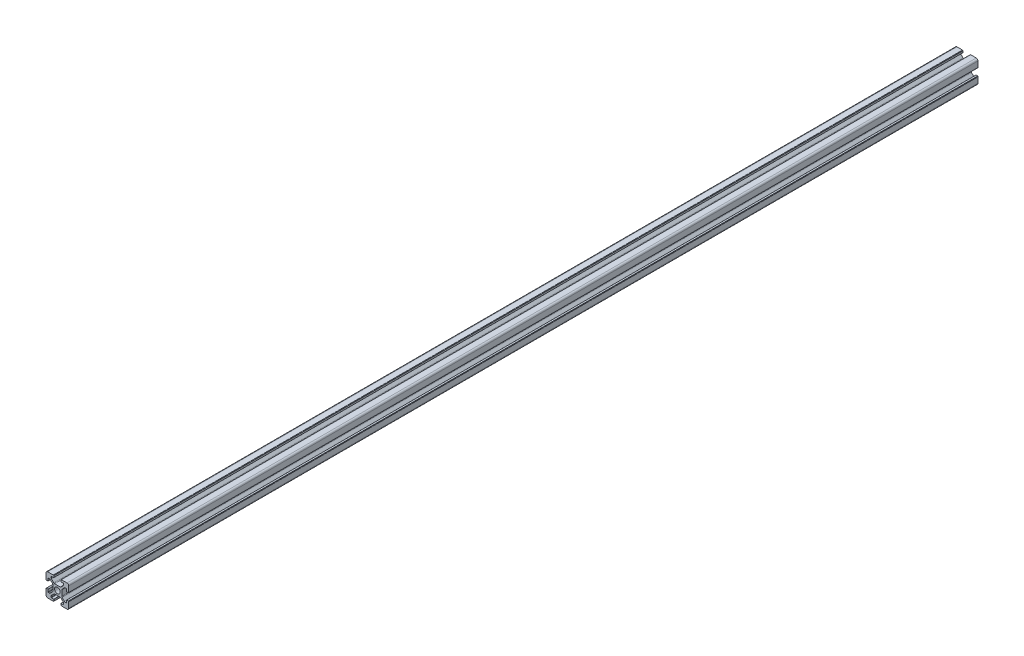
SolidWorks part; units mm, degrees
material "6063-T5"
ref_plane "前视基准面" through (0, 0, 0) normal (0, 0, 1) x (1, 0, 0)
ref_plane "上视基准面" through (0, 0, 0) normal (0, 1, 0) x (1, 0, 0)
ref_plane "右视基准面" through (0, 0, 0) normal (1, 0, 0) x (0, 0, -1)
sketch "草图1" plane through (0, 0, 0) normal (0, 0, 1) x (1, 0, 0)
  line L0 (-1.4389, 10) -> (24.3741, 10) construction
  line L1 (20, 13.6) -> (20, 20)
  line L2 (0, 0) -> (0, 6.4)
  line L3 (0, 20) -> (6.4, 20)
  line L4 (20, 0) -> (20, 6.4)
  line L5 (10, 21.5388) -> (10, -2.4017) construction
  line L6 (6.9, 18.3) -> (6.9, 19.7)
  line L7 (6.8, 18.2) -> (4.8, 18.2)
  line L8 (4.5, 17.9) -> (4.5, 16.9749)
  line L9 (4.7929, 16.2678) -> (6.8678, 14.1929)
  line L10 (7.5749, 13.9) -> (12.4251, 13.9)
  line L11 (6.8, 19.8) -> (6.4, 19.8)
  line L12 (6.4, 19.8) -> (6.4, 20)
  line L13 (0, 13.6) -> (0.2, 13.6)
  line L14 (0.2, 13.6) -> (0.2, 13.2)
  line L15 (0.3, 13.1) -> (1.7, 13.1)
  line L16 (1.8, 13.2) -> (1.8, 15.2)
  line L17 (2.1, 15.5) -> (3.0251, 15.5)
  line L18 (3.7322, 15.2071) -> (5.8071, 13.1322)
  line L19 (6.1, 12.4251) -> (6.1, 7.5749)
  line L20 (13.6, 19.8) -> (13.6, 20)
  line L21 (13.2, 19.8) -> (13.6, 19.8)
  line L22 (13.1, 18.3) -> (13.1, 19.7)
  line L23 (13.2, 18.2) -> (15.2, 18.2)
  line L24 (15.5, 17.9) -> (15.5, 16.9749)
  line L25 (15.2071, 16.2678) -> (13.1322, 14.1929)
  line L26 (0, 6.4) -> (0.2, 6.4)
  line L27 (0.2, 6.4) -> (0.2, 6.8)
  line L28 (0.3, 6.9) -> (1.7, 6.9)
  line L29 (1.8, 6.8) -> (1.8, 4.8)
  line L30 (2.1, 4.5) -> (3.0251, 4.5)
  line L31 (3.7322, 4.7929) -> (5.8071, 6.8678)
  line L32 (13.6, 20) -> (20, 20)
  line L33 (0, 13.6) -> (0, 20)
  line L34 (13.6, 0.2) -> (13.6, 0)
  line L35 (13.2, 0.2) -> (13.6, 0.2)
  line L36 (13.1, 1.7) -> (13.1, 0.3)
  line L37 (13.2, 1.8) -> (15.2, 1.8)
  line L38 (15.5, 2.1) -> (15.5, 3.0251)
  line L39 (15.2071, 3.7322) -> (13.1322, 5.8071)
  line L40 (4.5, 2.1) -> (4.5, 3.0251)
  line L41 (6.8, 1.8) -> (4.8, 1.8)
  line L42 (6.4, 0.2) -> (6.4, 0)
  line L43 (6.8, 0.2) -> (6.4, 0.2)
  line L44 (6.9, 1.7) -> (6.9, 0.3)
  line L45 (4.7929, 3.7322) -> (6.8678, 5.8071)
  line L46 (7.5749, 6.1) -> (12.4251, 6.1)
  line L47 (20, 6.4) -> (19.8, 6.4)
  line L48 (19.8, 6.4) -> (19.8, 6.8)
  line L49 (19.7, 6.9) -> (18.3, 6.9)
  line L50 (18.2, 6.8) -> (18.2, 4.8)
  line L51 (17.9, 4.5) -> (16.9749, 4.5)
  line L52 (16.2678, 4.7929) -> (14.1929, 6.8678)
  line L53 (13.9, 12.4251) -> (13.9, 7.5749)
  line L54 (16.2678, 15.2071) -> (14.1929, 13.1322)
  line L55 (17.9, 15.5) -> (16.9749, 15.5)
  line L56 (18.2, 13.2) -> (18.2, 15.2)
  line L57 (19.7, 13.1) -> (18.3, 13.1)
  line L58 (19.8, 13.6) -> (19.8, 13.2)
  line L59 (20, 13.6) -> (19.8, 13.6)
  line L60 (0, 0) -> (6.4, 0)
  line L61 (13.6, 0) -> (20, 0)
  arc A0 (6.1, 12.4251) -> (5.8071, 13.1322) centre (5.1, 12.4251) ccw
  arc A1 (7.5749, 13.9) -> (6.8678, 14.1929) centre (7.5749, 14.9) cw
  arc A2 (4.5, 16.9749) -> (4.7929, 16.2678) centre (5.5, 16.9749) ccw
  arc A3 (3.7322, 15.2071) -> (3.0251, 15.5) centre (3.0251, 14.5) ccw
  arc A4 (4.5, 17.9) -> (4.8, 18.2) centre (4.8, 17.9) cw
  arc A5 (1.8, 15.2) -> (2.1, 15.5) centre (2.1, 15.2) cw
  arc A6 (0.3, 13.1) -> (0.2, 13.2) centre (0.3, 13.2) cw
  arc A7 (6.9, 19.7) -> (6.8, 19.8) centre (6.8, 19.7) ccw
  arc A8 (1.7, 13.1) -> (1.8, 13.2) centre (1.7, 13.2) ccw
  arc A9 (6.9, 18.3) -> (6.8, 18.2) centre (6.8, 18.3) cw
  arc A10 (13.1, 19.7) -> (13.2, 19.8) centre (13.2, 19.7) cw
  arc A11 (13.1, 18.3) -> (13.2, 18.2) centre (13.2, 18.3) ccw
  arc A12 (15.5, 17.9) -> (15.2, 18.2) centre (15.2, 17.9) ccw
  arc A13 (15.5, 16.9749) -> (15.2071, 16.2678) centre (14.5, 16.9749) cw
  arc A14 (12.4251, 13.9) -> (13.1322, 14.1929) centre (12.4251, 14.9) ccw
  arc A15 (0.3, 6.9) -> (0.2, 6.8) centre (0.3, 6.8) ccw
  arc A16 (1.7, 6.9) -> (1.8, 6.8) centre (1.7, 6.8) cw
  arc A17 (1.8, 4.8) -> (2.1, 4.5) centre (2.1, 4.8) ccw
  arc A18 (3.7322, 4.7929) -> (3.0251, 4.5) centre (3.0251, 5.5) cw
  arc A19 (6.1, 7.5749) -> (5.8071, 6.8678) centre (5.1, 7.5749) cw
  arc A20 (13.1, 0.3) -> (13.2, 0.2) centre (13.2, 0.3) ccw
  arc A21 (13.1, 1.7) -> (13.2, 1.8) centre (13.2, 1.7) cw
  arc A22 (15.5, 2.1) -> (15.2, 1.8) centre (15.2, 2.1) cw
  arc A23 (15.5, 3.0251) -> (15.2071, 3.7322) centre (14.5, 3.0251) ccw
  arc A24 (12.4251, 6.1) -> (13.1322, 5.8071) centre (12.4251, 5.1) cw
  arc A25 (4.5, 2.1) -> (4.8, 1.8) centre (4.8, 2.1) ccw
  arc A26 (6.9, 0.3) -> (6.8, 0.2) centre (6.8, 0.3) cw
  arc A27 (6.9, 1.7) -> (6.8, 1.8) centre (6.8, 1.7) ccw
  arc A28 (4.5, 3.0251) -> (4.7929, 3.7322) centre (5.5, 3.0251) cw
  arc A29 (7.5749, 6.1) -> (6.8678, 5.8071) centre (7.5749, 5.1) ccw
  arc A30 (19.7, 6.9) -> (19.8, 6.8) centre (19.7, 6.8) cw
  arc A31 (18.3, 6.9) -> (18.2, 6.8) centre (18.3, 6.8) ccw
  arc A32 (18.2, 4.8) -> (17.9, 4.5) centre (17.9, 4.8) cw
  arc A33 (16.2678, 4.7929) -> (16.9749, 4.5) centre (16.9749, 5.5) ccw
  arc A34 (13.9, 7.5749) -> (14.1929, 6.8678) centre (14.9, 7.5749) ccw
  arc A35 (13.9, 12.4251) -> (14.1929, 13.1322) centre (14.9, 12.4251) cw
  arc A36 (16.2678, 15.2071) -> (16.9749, 15.5) centre (16.9749, 14.5) cw
  arc A37 (18.2, 15.2) -> (17.9, 15.5) centre (17.9, 15.2) ccw
  arc A38 (18.3, 13.1) -> (18.2, 13.2) centre (18.3, 13.2) cw
  arc A39 (19.7, 13.1) -> (19.8, 13.2) centre (19.7, 13.2) ccw
  circle A40 centre (10, 10) radius 2.5
  point P39 (0.2, 13.1)
  point P42 (6.9, 19.8)
  point P45 (1.8, 13.1)
  point P48 (6.9, 18.2)
  point P66 (10, 13.9)
  point P83 (6.1, 10)
  dimension "D19" = 1
  dimension "D20" = 1
  dimension "D21" = 0.3
  dimension "D22" = 0.1
  dimension "D23" = 5
  dimension "D1" = 20
  dimension "D2" = 20
  dimension "D3" = 10
  dimension "D4" = 10
  dimension "D5" = 1.8
  dimension "D6" = 0.5
  dimension "D7" = 1.6
  dimension "D8" = 3.1
  dimension "D9" = 6.1
  dimension "D10" = 5.5
  dimension "D11" = 3.1
  dimension "D12" = 6.1
  dimension "D13" = 5.5
  dimension "D14" = 1.8
  dimension "D15" = 0.5
  dimension "D16" = 1.5
  dimension "D17" = 45
  dimension "D18" = 1.6
extrude "凸台-拉伸1" add sketch "草图1" along normal blind 800
fillet "圆角1" radius 1.5 4 edges at (20, 0, 400) (0, 0, 400) (0, 20, 400) (20, 20, 400)
